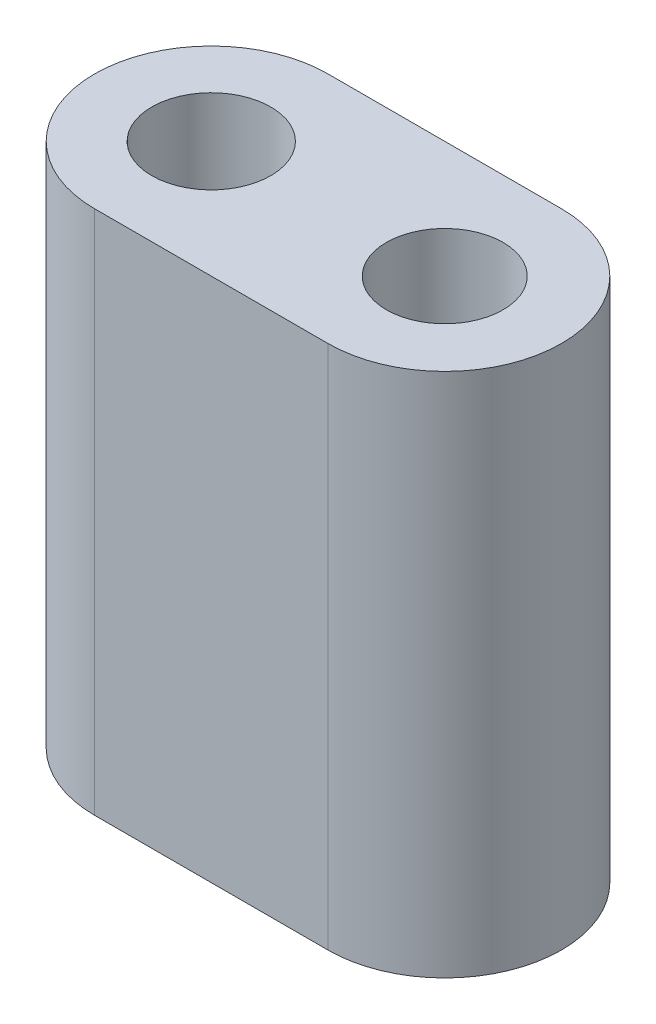
SolidWorks part; units mm, degrees
ref_plane "Front Plane" through (0, 0, 0) normal (0, 0, 1) x (1, 0, 0)
ref_plane "Top Plane" through (0, 0, 0) normal (0, 1, 0) x (1, 0, 0)
ref_plane "Right Plane" through (0, 0, 0) normal (1, 0, 0) x (0, 0, -1)
sketch "Sketch1" plane through (0, 0, 0) normal (0, 1, 0) x (1, 0, 0)
  line L0 (0, 0) -> (12.7, 0) construction
  line L1 (0, 6.35) -> (12.7, 6.35)
  line L2 (0, -6.35) -> (12.7, -6.35)
  arc A0 (0, 6.35) -> (0, -6.35) centre (0, 0) ccw
  arc A1 (12.7, -6.35) -> (12.7, 6.35) centre (12.7, 0) ccw
  circle A2 centre (0, 0) radius 3.2385
  circle A3 centre (0, 0) radius 3.175 construction
  circle A4 centre (12.7, 0) radius 3.175
  point P3 (6.35, 0)
  dimension "D2" = 6.477
  dimension "D3" = 6.35
  dimension "D5" = 6.35
  dimension "D1" = 12.7
  dimension "D4" = 12.7
extrude "Boss-Extrude1" add sketch "Sketch1" along normal blind 28.575
sketch "Sketch2" plane through (0, 0, 0) normal (0, -1, 0) x (1, 0, 0)
  circle A0 centre (12.7, 0) radius 2.3813
  circle A1 centre (12.7, 0) radius 3.175 construction
  circle A2 centre (12.7, 0) radius 3.175
  dimension "D1" = 0.7937
extrude "Boss-Extrude2" add sketch "Sketch2" against normal blind 3.175
